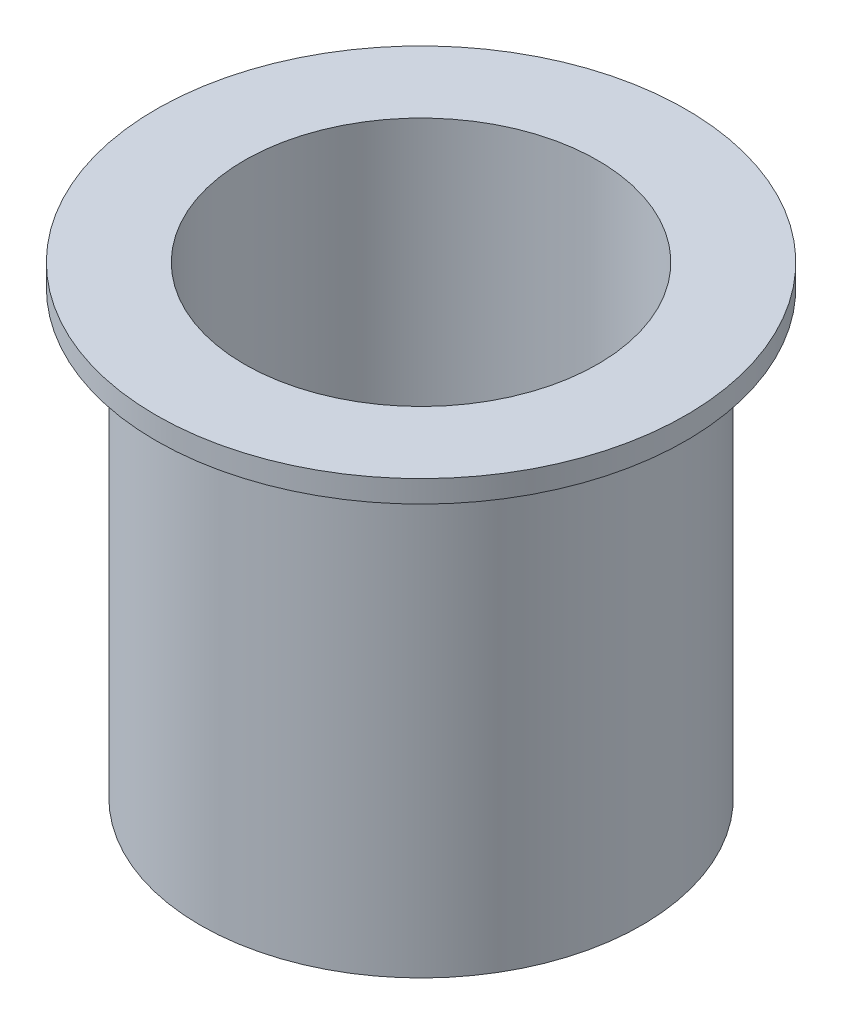
SolidWorks part; units mm, degrees
ref_plane "Front Plane" through (0, 0, 0) normal (0, 0, 1) x (1, 0, 0)
ref_plane "Top Plane" through (0, 0, 0) normal (0, 1, 0) x (1, 0, 0)
ref_plane "Right Plane" through (0, 0, 0) normal (1, 0, 0) x (0, 0, -1)
sketch "Sketch2" plane through (0, 0, 0) normal (0, 1, 0) x (1, 0, 0)
  circle A0 centre (0, 0) radius 8
  circle A1 centre (0, 0) radius 10
extrude "Boss-Extrude1" add sketch "Sketch2" against normal blind 20 contours A1 | A0
sketch "Sketch3" plane through (0, 0, 0) normal (0, 1, 0) x (1, 0, 0)
  circle A0 centre (0, 0) radius 12
  circle A1 centre (0, 0) radius 8
extrude "Boss-Extrude2" add sketch "Sketch3" along normal blind 1
